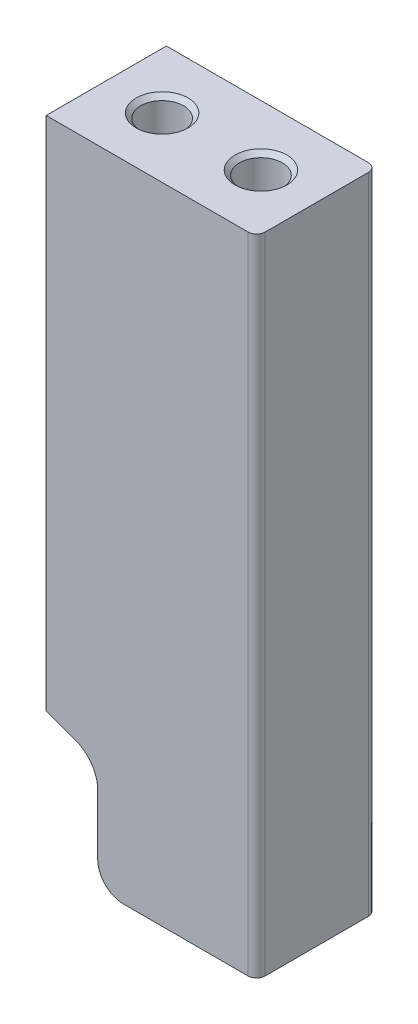
SolidWorks part; units mm, degrees
material "K110"
ref_plane "Front Plane" through (0, 0, 0) normal (0, 0, 1) x (1, 0, 0)
ref_plane "Top Plane" through (0, 0, 0) normal (0, 1, 0) x (1, 0, 0)
ref_plane "Right Plane" through (0, 0, 0) normal (1, 0, 0) x (0, 0, -1)
sketch "Sketch1" plane through (0, 0, 0) normal (0, 1, 0) x (1, 0, 0)
  line L1 (-12.25, -7) -> (12.25, -7)
  line L2 (-12.25, -7) -> (-12.25, 7)
  line L3 (-12.25, 7) -> (12.25, 7)
  line L4 (12.25, -7) -> (12.25, 7)
  line L5 (-12.25, -7) -> (12.25, 7) construction
  line L6 (-12.25, 7) -> (12.25, -7) construction
  point P0 (0, 0)
  dimension "D1" = 24.5
  dimension "D2" = 14
extrude "Boss-Extrude1" add sketch "Sketch1" against normal blind 75
sketch "Sketch2" plane through (0, 0, 7) normal (0, 0, 1) x (1, 0, 0)
  line L0 (-12.25, 0) -> (12.25, 0) construction
  line L1 (-12.25, -75) -> (-6.25, -75) construction
  line L2 (-12.25, -75) -> (-12.25, -61) construction
  line L3 (-12.25, -61) -> (-10.25, -61) construction
  line L4 (-6.25, -75) -> (-6.25, -65) construction
  line L5 (12.25, -75) -> (12.25, 0) construction
  line L6 (-8.8819, -61.2412) -> (-12.25, -60.0153)
  line L7 (-12.25, -75) -> (-12.25, 0) construction
  line L8 (-6.25, -65) -> (-6.25, -75)
  line L9 (-6.25, -75) -> (-12.25, -75)
  line L10 (-12.25, -75) -> (-12.25, -60.0153)
  arc A0 (-10.25, -61) -> (-6.25, -65) centre (-10.25, -65) cw construction
  arc A1 (-6.25, -65) -> (-8.8819, -61.2412) centre (-10.25, -65) ccw
  dimension "D3" = 4
  dimension "D1" = 61
  dimension "D2" = 18.5
  dimension "D4" = 2
  dimension "D5" = 20
extrude "Cut-Extrude1" cut sketch "Sketch2" against normal up to next
fillet "Fillet1" radius 3 1 edges at (-6.25, -75, 0)
fillet "Fillet2" radius 1 2 edges at (12.25, -37.5, -7) (12.25, -37.5, 7)
hole_wizard "M6 Tapped Hole1" positions "Sketch6" profile "Sketch4" tap size "M6" standard "ISO"
sketch "Sketch6" plane through (0, 0, 0) normal (0, 1, 0) x (1, 0, 0)
  line L0 (-12.25, 7) -> (-12.25, -7) construction
  line L1 (12.25, -6) -> (12.25, 6) construction
  point P0 (-5.75, 0)
  point P2 (5.75, 0)
  dimension "D1" = 6.5
  dimension "D2" = 6.5
sketch "Sketch4" plane through (-5.75, 0, 0) normal (1, 0, 0) x (0, 0, 1)
  line L0 (0, 0) -> (0, 18.5022)
  line L1 (0, 18.5022) -> (2.5, 17)
  line L2 (2.5, 17) -> (2.5, 0.525)
  line L3 (2.5, 0.525) -> (3.025, 0)
  line L5 (3.025, 0) -> (0, 0)
  line L6 (-2.5, 0.525) -> (-3.025, 0) construction
  line L10 (0, 18.5022) -> (-2.5, 17) construction
  line L11 (0, -6.35) -> (0, 107.95) construction
  dimension "Tap Drill Dia." = 5
  dimension "Tap Drill Depth" = 17
  dimension "Near C'Sink Dia." = 6.05
  dimension "Near C'Sink Angle" = 90
  dimension "Drill Angle" = 118
cosmetic thread "Hole Thread1" parameters "D1"=12, "D2"=6
cosmetic thread "Hole Thread2" parameters "D1"=12, "D2"=6
ref_plane "Plane1" through (0, -50, 0) normal (0, 1, 0) x (1, 0, 0)
sketch "Sketch7" plane through (0, -50, 0) normal (0, 1, 0) x (1, 0, 0)
  line L0 (-12.25, -7) -> (11.25, -7)
  line L1 (-12.25, -7) -> (11.25, -7)
  line L2 (12.25, -6) -> (12.25, 6)
  line L3 (12.25, -6) -> (12.25, 6)
  line L4 (11.25, 7) -> (-12.25, 7)
  line L5 (11.25, 7) -> (-12.25, 7)
  line L6 (-12.25, 7) -> (-12.25, -7)
  line L7 (-12.25, 7) -> (-12.25, -7)
  arc A0 (11.25, -7) -> (12.25, -6) centre (11.25, -6) ccw
  arc A1 (11.25, -7) -> (12.25, -6) centre (11.25, -6) ccw
  arc A2 (12.25, 6) -> (11.25, 7) centre (11.25, 6) ccw
  arc A3 (12.25, 6) -> (11.25, 7) centre (11.25, 6) ccw
